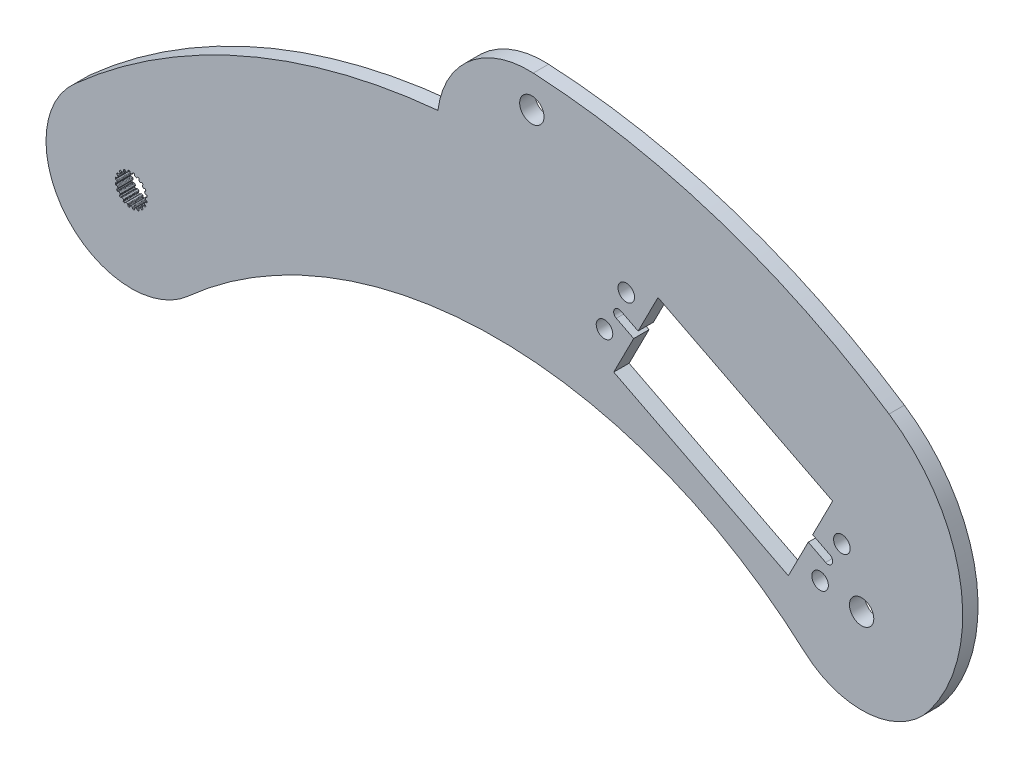
SolidWorks part; units mm, degrees
ref_plane "Front Plane" through (0, 0, 0) normal (0, 0, 1) x (1, 0, 0)
ref_plane "Top Plane" through (0, 0, 0) normal (0, 1, 0) x (1, 0, 0)
ref_plane "Right Plane" through (0, 0, 0) normal (1, 0, 0) x (0, 0, -1)
sketch "Sketch1" plane through (0, 0, 0) normal (0, 0, 1) x (1, 0, 0)
  line L0 (-0.1069, 2.9699) -> (0.1069, 2.9699)
  line L1 (0.3159, 3.2375) -> (0.2537, 3.0575)
  line L2 (-0.2964, 3.2367) -> (-0.2318, 3.0575)
  line L3 (-0.2964, 3.2367) -> (0.3159, 3.2375) construction
  line L4 (0, 3.3252) -> (0, 0) construction
  line L5 (-0.2318, 3.0575) -> (0.2537, 3.0575) construction
  line L6 (-0.4281, 3.3241) -> (0.4281, 3.3263) construction
  line L7 (0.7183, 3.1698) -> (0.7244, 2.9795)
  line L8 (0.816, 2.8576) -> (1.0195, 2.7915)
  line L9 (1.3009, 2.9815) -> (1.1862, 2.8295)
  line L10 (1.6627, 2.7927) -> (1.6097, 2.6099)
  line L11 (1.6591, 2.4655) -> (1.8322, 2.3398)
  line L12 (2.1585, 2.4335) -> (2.0025, 2.3245)
  line L13 (2.4443, 2.1423) -> (2.3374, 1.9847)
  line L14 (2.3398, 1.8322) -> (2.4655, 1.6591)
  line L15 (2.8049, 1.6474) -> (2.6228, 1.5919)
  line L16 (2.9866, 1.2821) -> (2.8363, 1.1653)
  line L17 (2.7915, 1.0195) -> (2.8576, 0.816)
  line L18 (3.1767, 0.7) -> (2.9863, 0.7035)
  line L19 (3.2367, 0.2964) -> (3.0575, 0.2318)
  line L20 (2.9699, 0.1069) -> (2.9699, -0.1069)
  line L21 (3.2375, -0.3159) -> (3.0575, -0.2537)
  line L22 (3.1698, -0.7183) -> (2.9795, -0.7244)
  line L23 (2.8576, -0.816) -> (2.7915, -1.0195)
  line L24 (2.9815, -1.3009) -> (2.8295, -1.1862)
  line L25 (2.7927, -1.6627) -> (2.6099, -1.6097)
  line L26 (2.4655, -1.6591) -> (2.3398, -1.8322)
  line L27 (2.4335, -2.1585) -> (2.3245, -2.0025)
  line L28 (2.1423, -2.4443) -> (1.9847, -2.3374)
  line L29 (1.8322, -2.3398) -> (1.6591, -2.4655)
  line L30 (1.6474, -2.8049) -> (1.5919, -2.6228)
  line L31 (1.2821, -2.9866) -> (1.1653, -2.8363)
  line L32 (1.0195, -2.7915) -> (0.816, -2.8576)
  line L33 (0.7, -3.1767) -> (0.7035, -2.9863)
  line L34 (0.2964, -3.2367) -> (0.2318, -3.0575)
  line L35 (0.1069, -2.9699) -> (-0.1069, -2.9699)
  line L36 (-0.3159, -3.2375) -> (-0.2537, -3.0575)
  line L37 (-0.7183, -3.1698) -> (-0.7244, -2.9795)
  line L38 (-0.816, -2.8576) -> (-1.0195, -2.7915)
  line L39 (-1.3009, -2.9815) -> (-1.1862, -2.8295)
  line L40 (-1.6627, -2.7927) -> (-1.6097, -2.6099)
  line L41 (-1.6591, -2.4655) -> (-1.8322, -2.3398)
  line L42 (-2.1585, -2.4335) -> (-2.0025, -2.3245)
  line L43 (-2.4443, -2.1423) -> (-2.3374, -1.9847)
  line L44 (-2.3398, -1.8322) -> (-2.4655, -1.6591)
  line L45 (-2.8049, -1.6474) -> (-2.6228, -1.5919)
  line L46 (-2.9866, -1.2821) -> (-2.8363, -1.1653)
  line L47 (-2.7915, -1.0195) -> (-2.8576, -0.816)
  line L48 (-3.1767, -0.7) -> (-2.9863, -0.7035)
  line L49 (-3.2367, -0.2964) -> (-3.0575, -0.2318)
  line L50 (-2.9699, -0.1069) -> (-2.9699, 0.1069)
  line L51 (-3.2375, 0.3159) -> (-3.0575, 0.2537)
  line L52 (-3.1698, 0.7183) -> (-2.9795, 0.7244)
  line L53 (-2.8576, 0.816) -> (-2.7915, 1.0195)
  line L54 (-2.9815, 1.3009) -> (-2.8295, 1.1862)
  line L55 (-2.7927, 1.6627) -> (-2.6099, 1.6097)
  line L56 (-2.4655, 1.6591) -> (-2.3398, 1.8322)
  line L57 (-2.4335, 2.1585) -> (-2.3245, 2.0025)
  line L58 (-2.1423, 2.4443) -> (-1.9847, 2.3374)
  line L59 (-1.8322, 2.3398) -> (-1.6591, 2.4655)
  line L60 (-1.6474, 2.8049) -> (-1.5919, 2.6228)
  line L61 (-1.2821, 2.9866) -> (-1.1653, 2.8363)
  line L62 (-1.0195, 2.7915) -> (-0.816, 2.8576)
  line L63 (-0.7, 3.1767) -> (-0.7035, 2.9863)
  line L64 (0.4281, 3.3263) -> (0.62, 3.2938)
  line L65 (1.4351, 3.0312) -> (1.6075, 2.9409)
  line L66 (2.3015, 2.4394) -> (2.4376, 2.3003)
  line L67 (2.9427, 1.6088) -> (3.0291, 1.4344)
  line L68 (3.2958, 0.6207) -> (3.3241, 0.4281)
  line L69 (3.3263, -0.4281) -> (3.2938, -0.62)
  line L70 (3.0312, -1.4351) -> (2.9409, -1.6075)
  line L71 (2.4394, -2.3015) -> (2.3003, -2.4376)
  line L72 (1.6088, -2.9427) -> (1.4344, -3.0291)
  line L73 (0.6207, -3.2958) -> (0.4281, -3.3241)
  line L74 (-0.4281, -3.3263) -> (-0.62, -3.2938)
  line L75 (-1.4351, -3.0312) -> (-1.6075, -2.9409)
  line L76 (-2.3015, -2.4394) -> (-2.4376, -2.3003)
  line L77 (-2.9427, -1.6088) -> (-3.0291, -1.4344)
  line L78 (-3.2958, -0.6207) -> (-3.3241, -0.4281)
  line L79 (-3.3263, 0.4281) -> (-3.2938, 0.62)
  line L80 (-3.0312, 1.4351) -> (-2.9409, 1.6075)
  line L81 (-2.4394, 2.3015) -> (-2.3003, 2.4376)
  line L82 (-1.6088, 2.9427) -> (-1.4344, 3.0291)
  line L83 (-0.6207, 3.2958) -> (-0.4281, 3.3241)
  line L84 (-11.8753, 13.2369) -> (11.8753, -13.2369) construction
  line L85 (164.2753, 13.2369) -> (140.5247, -13.2369) construction
  line L86 (0, 0) -> (152.4, 0) construction
  arc A0 (0.2537, 3.0575) -> (0.1069, 2.9699) centre (0.1283, 3.1009) cw
  arc A1 (-0.2318, 3.0575) -> (-0.1069, 2.9699) centre (-0.1069, 3.1026) ccw
  arc A2 (0.62, 3.2938) -> (0.7183, 3.1698) centre (0.5856, 3.1656) cw
  arc A3 (0.7244, 2.9795) -> (0.816, 2.8576) centre (0.857, 2.9838) ccw
  arc A4 (-0.4281, 3.3241) -> (-0.2964, 3.2367) centre (-0.4213, 3.1916) cw
  arc A5 (0.4281, 3.3263) -> (0.3159, 3.2375) centre (0.4413, 3.1942) ccw
  arc A6 (1.1862, 2.8295) -> (1.0195, 2.7915) centre (1.0802, 2.9095) cw
  arc A7 (1.4351, 3.0312) -> (1.3009, 2.9815) centre (1.4068, 2.9015) ccw
  arc A8 (1.6075, 2.9409) -> (1.6627, 2.7927) centre (1.5352, 2.8297) cw
  arc A9 (1.6097, 2.6099) -> (1.6591, 2.4655) centre (1.7371, 2.5729) ccw
  arc A10 (2.0025, 2.3245) -> (1.8322, 2.3398) centre (1.9264, 2.4332) cw
  arc A11 (2.3015, 2.4394) -> (2.1585, 2.4335) centre (2.2346, 2.3248) ccw
  arc A12 (2.4376, 2.3003) -> (2.4443, 2.1423) centre (2.3345, 2.2168) cw
  arc A13 (2.3374, 1.9847) -> (2.3398, 1.8322) centre (2.4472, 1.9102) ccw
  arc A14 (2.6228, 1.5919) -> (2.4655, 1.6591) centre (2.5841, 1.7189) cw
  arc A15 (2.9427, 1.6088) -> (2.8049, 1.6474) centre (2.8436, 1.5205) ccw
  arc A16 (3.0291, 1.4344) -> (2.9866, 1.2821) centre (2.9052, 1.3869) cw
  arc A17 (2.8363, 1.1653) -> (2.7915, 1.0195) centre (2.9177, 1.0605) ccw
  arc A18 (2.9863, 0.7035) -> (2.8576, 0.816) centre (2.9887, 0.8362) cw
  arc A19 (3.2958, 0.6207) -> (3.1767, 0.7) centre (3.1743, 0.5673) ccw
  arc A20 (3.3241, 0.4281) -> (3.2367, 0.2964) centre (3.1916, 0.4213) cw
  arc A21 (3.0575, 0.2318) -> (2.9699, 0.1069) centre (3.1026, 0.1069) ccw
  arc A22 (3.0575, -0.2537) -> (2.9699, -0.1069) centre (3.1009, -0.1283) cw
  arc A23 (3.3263, -0.4281) -> (3.2375, -0.3159) centre (3.1942, -0.4413) ccw
  arc A24 (3.2938, -0.62) -> (3.1698, -0.7183) centre (3.1656, -0.5856) cw
  arc A25 (2.9795, -0.7244) -> (2.8576, -0.816) centre (2.9838, -0.857) ccw
  arc A26 (2.8295, -1.1862) -> (2.7915, -1.0195) centre (2.9095, -1.0802) cw
  arc A27 (3.0312, -1.4351) -> (2.9815, -1.3009) centre (2.9015, -1.4068) ccw
  arc A28 (2.9409, -1.6075) -> (2.7927, -1.6627) centre (2.8297, -1.5352) cw
  arc A29 (2.6099, -1.6097) -> (2.4655, -1.6591) centre (2.5729, -1.7371) ccw
  arc A30 (2.3245, -2.0025) -> (2.3398, -1.8322) centre (2.4332, -1.9264) cw
  arc A31 (2.4394, -2.3015) -> (2.4335, -2.1585) centre (2.3248, -2.2346) ccw
  arc A32 (2.3003, -2.4376) -> (2.1423, -2.4443) centre (2.2168, -2.3345) cw
  arc A33 (1.9847, -2.3374) -> (1.8322, -2.3398) centre (1.9102, -2.4472) ccw
  arc A34 (1.5919, -2.6228) -> (1.6591, -2.4655) centre (1.7189, -2.5841) cw
  arc A35 (1.6088, -2.9427) -> (1.6474, -2.8049) centre (1.5205, -2.8436) ccw
  arc A36 (1.4344, -3.0291) -> (1.2821, -2.9866) centre (1.3869, -2.9052) cw
  arc A37 (1.1653, -2.8363) -> (1.0195, -2.7915) centre (1.0605, -2.9177) ccw
  arc A38 (0.7035, -2.9863) -> (0.816, -2.8576) centre (0.8362, -2.9887) cw
  arc A39 (0.6207, -3.2958) -> (0.7, -3.1767) centre (0.5673, -3.1743) ccw
  arc A40 (0.4281, -3.3241) -> (0.2964, -3.2367) centre (0.4213, -3.1916) cw
  arc A41 (0.2318, -3.0575) -> (0.1069, -2.9699) centre (0.1069, -3.1026) ccw
  arc A42 (-0.2537, -3.0575) -> (-0.1069, -2.9699) centre (-0.1283, -3.1009) cw
  arc A43 (-0.4281, -3.3263) -> (-0.3159, -3.2375) centre (-0.4413, -3.1942) ccw
  arc A44 (-0.62, -3.2938) -> (-0.7183, -3.1698) centre (-0.5856, -3.1656) cw
  arc A45 (-0.7244, -2.9795) -> (-0.816, -2.8576) centre (-0.857, -2.9838) ccw
  arc A46 (-1.1862, -2.8295) -> (-1.0195, -2.7915) centre (-1.0802, -2.9095) cw
  arc A47 (-1.4351, -3.0312) -> (-1.3009, -2.9815) centre (-1.4068, -2.9015) ccw
  arc A48 (-1.6075, -2.9409) -> (-1.6627, -2.7927) centre (-1.5352, -2.8297) cw
  arc A49 (-1.6097, -2.6099) -> (-1.6591, -2.4655) centre (-1.7371, -2.5729) ccw
  arc A50 (-2.0025, -2.3245) -> (-1.8322, -2.3398) centre (-1.9264, -2.4332) cw
  arc A51 (-2.3015, -2.4394) -> (-2.1585, -2.4335) centre (-2.2346, -2.3248) ccw
  arc A52 (-2.4376, -2.3003) -> (-2.4443, -2.1423) centre (-2.3345, -2.2168) cw
  arc A53 (-2.3374, -1.9847) -> (-2.3398, -1.8322) centre (-2.4472, -1.9102) ccw
  arc A54 (-2.6228, -1.5919) -> (-2.4655, -1.6591) centre (-2.5841, -1.7189) cw
  arc A55 (-2.9427, -1.6088) -> (-2.8049, -1.6474) centre (-2.8436, -1.5205) ccw
  arc A56 (-3.0291, -1.4344) -> (-2.9866, -1.2821) centre (-2.9052, -1.3869) cw
  arc A57 (-2.8363, -1.1653) -> (-2.7915, -1.0195) centre (-2.9177, -1.0605) ccw
  arc A58 (-2.9863, -0.7035) -> (-2.8576, -0.816) centre (-2.9887, -0.8362) cw
  arc A59 (-3.2958, -0.6207) -> (-3.1767, -0.7) centre (-3.1743, -0.5673) ccw
  arc A60 (-3.3241, -0.4281) -> (-3.2367, -0.2964) centre (-3.1916, -0.4213) cw
  arc A61 (-3.0575, -0.2318) -> (-2.9699, -0.1069) centre (-3.1026, -0.1069) ccw
  arc A62 (-3.0575, 0.2537) -> (-2.9699, 0.1069) centre (-3.1009, 0.1283) cw
  arc A63 (-3.3263, 0.4281) -> (-3.2375, 0.3159) centre (-3.1942, 0.4413) ccw
  arc A64 (-3.2938, 0.62) -> (-3.1698, 0.7183) centre (-3.1656, 0.5856) cw
  arc A65 (-2.9795, 0.7244) -> (-2.8576, 0.816) centre (-2.9838, 0.857) ccw
  arc A66 (-2.8295, 1.1862) -> (-2.7915, 1.0195) centre (-2.9095, 1.0802) cw
  arc A67 (-3.0312, 1.4351) -> (-2.9815, 1.3009) centre (-2.9015, 1.4068) ccw
  arc A68 (-2.9409, 1.6075) -> (-2.7927, 1.6627) centre (-2.8297, 1.5352) cw
  arc A69 (-2.6099, 1.6097) -> (-2.4655, 1.6591) centre (-2.5729, 1.7371) ccw
  arc A70 (-2.3245, 2.0025) -> (-2.3398, 1.8322) centre (-2.4332, 1.9264) cw
  arc A71 (-2.4394, 2.3015) -> (-2.4335, 2.1585) centre (-2.3248, 2.2346) ccw
  arc A72 (-2.3003, 2.4376) -> (-2.1423, 2.4443) centre (-2.2168, 2.3345) cw
  arc A73 (-1.9847, 2.3374) -> (-1.8322, 2.3398) centre (-1.9102, 2.4472) ccw
  arc A74 (-1.5919, 2.6228) -> (-1.6591, 2.4655) centre (-1.7189, 2.5841) cw
  arc A75 (-1.6088, 2.9427) -> (-1.6474, 2.8049) centre (-1.5205, 2.8436) ccw
  arc A76 (-1.4344, 3.0291) -> (-1.2821, 2.9866) centre (-1.3869, 2.9052) cw
  arc A77 (-1.1653, 2.8363) -> (-1.0195, 2.7915) centre (-1.0605, 2.9177) ccw
  arc A78 (-0.7035, 2.9863) -> (-0.816, 2.8576) centre (-0.8362, 2.9887) cw
  arc A79 (-0.6207, 3.2958) -> (-0.7, 3.1767) centre (-0.5673, 3.1743) ccw
  circle A80 centre (0, 0) radius 12.7 construction
  arc A81 (-11.8753, 13.2369) -> (164.2753, 13.2369) centre (76.2, -84.9368) cw
  arc A82 (11.8753, -13.2369) -> (140.5247, -13.2369) centre (76.2, -84.9368) cw
  arc A84 (-11.8753, 13.2369) -> (11.8753, -13.2369) centre (0, 0) ccw
  arc A85 (164.2753, 13.2369) -> (140.5247, -13.2369) centre (152.4, 0) cw
  point P14 (0, 2.9699)
  point P26 (0, 0)
  point P247 (0, 0)
  dimension "D4" = 0.1327
  dimension "D8" = 20
  dimension "D9" = 25.4
  dimension "D10" = 131.8914
  dimension "D1" = 2.9699
  dimension "D2" = 0.2139
  dimension "D3" = 0.1904
  dimension "D5" = 0.0877
  dimension "D6" = 0.4855
  dimension "D7" = 0.8563
  dimension "D11" = 35.5662
  dimension "D12" = 152.4
extrude "Boss-Extrude1" add sketch "Sketch1" along normal blind 3.2004
sketch "Sketch2" plane through (0, 0, 3.2004) normal (0, 0, 1) x (1, 0, 0)
  line L0 (132.2879, 12.7254) -> (132.9641, 14.0508) construction
  line L5 (128.1311, 26.252) -> (118.8966, 8.1515) construction
  line L7 (109.9175, 35.5442) -> (146.3447, 16.9598)
  line L13 (109.9175, 35.5442) -> (100.683, 17.4437)
  line L19 (98.7496, 24.2228) -> (103.2942, 33.1305) construction
  line L20 (143.7335, 1.273) -> (148.2781, 10.1807) construction
  line L24 (101.0219, 28.6767) -> (146.0058, 5.7268) construction
  line L30 (100.683, 17.4437) -> (137.1102, -1.1407)
  line L31 (146.3447, 16.9598) -> (137.1102, -1.1407)
  circle A7 centre (103.2942, 33.1305) radius 1.7272
  circle A9 centre (143.7335, 1.273) radius 1.7272
  circle A10 centre (148.2781, 10.1807) radius 1.7272
  circle A11 centre (98.7496, 24.2228) radius 1.7272
  circle A13 centre (132.2879, 12.7254) radius 3.429 construction
  arc A14 (0, 0) -> (152.4, 0) centre (76.2, -84.9368) cw construction
  arc A15 (-11.8753, 13.2369) -> (11.8753, -13.2369) centre (0, 0) ccw construction
  arc A16 (140.5247, -13.2369) -> (164.2753, 13.2369) centre (152.4, 0) ccw construction
  arc A17 (164.2753, 13.2369) -> (-11.8753, 13.2369) centre (76.2, -84.9368) ccw construction
  circle A18 centre (152.4, 0) radius 2.54
  point P0 (132.2879, 12.7254)
  point P1 (99.9946, 26.663)
  point P24 (123.5139, 17.2018)
  dimension "D2" = 15.4
  dimension "D3" = 6.858
  dimension "D5" = 3.4544
  dimension "D10" = 5.08
  dimension "D6" = 2.2606
  dimension "D8" = 20.32
  dimension "D13" = 23.7998
  dimension "D1" = 50.5
  dimension "D4" = 10
  dimension "D7" = 1.4879
  dimension "D9" = 40.894
extrude "Cut-Extrude1" cut sketch "Sketch2" against normal up to surface (3.2004 mm away) up to face at (76.2, 8.6481, 0)
sketch "Sketch3" plane through (0, 0, 3.2004) normal (0, 0, 1) x (1, 0, 0)
  line L0 (146.3447, 16.9598) -> (137.1102, -1.1407) construction
  line L1 (109.9175, 35.5442) -> (100.683, 17.4437) construction
  line L4 (102.1419, 29.2459) -> (105.762, 27.399)
  line L5 (102.1419, 29.2459) -> (101.2184, 27.4358) construction
  line L7 (101.2184, 27.4358) -> (104.8385, 25.5889)
  line L8 (105.762, 27.399) -> (104.8385, 25.5889)
  line L9 (142.1892, 8.8146) -> (145.8093, 6.9677)
  line L10 (142.1892, 8.8146) -> (141.2657, 7.0045)
  line L11 (141.2657, 7.0045) -> (144.8858, 5.1576)
  line L12 (145.8093, 6.9677) -> (144.8858, 5.1576) construction
  arc A6 (145.8093, 6.9677) -> (144.8858, 5.1576) centre (145.3475, 6.0627) cw
  arc A7 (102.1419, 29.2459) -> (101.2184, 27.4358) centre (101.6802, 28.3409) ccw
  point P22 (105.3003, 26.494)
  point P23 (141.7274, 7.9096)
  dimension "D4" = 4.064
  dimension "D5" = 2.032
extrude "Cut-Extrude2" cut sketch "Sketch3" against normal up to surface (3.2004 mm away) up to face at (97.0224, 24.2228, 0)
sketch "Sketch4" plane through (0, 0, 3.2004) normal (0, 0, 1) x (1, 0, 0)
  line L1 (83.5881, 56.2861) -> (152.4, 0) construction
  line L2 (83.5881, 56.2861) -> (83.1655, 46.7705) construction
  line L4 (158.1231, 38.5869) -> (166.6312, -10.6636) construction
  line L5 (83.89, 63.0847) -> (63.9945, 46.3886) construction
  arc A0 (63.9945, 46.3886) -> (83.89, 63.0847) centre (82.9016, 44.0604) cw
  arc A1 (164.2753, 13.2369) -> (-11.8753, 13.2369) centre (76.2, -84.9368) ccw construction
  circle A3 centre (152.4, 0) radius 2.54 construction
  circle A4 centre (83.5881, 56.2861) radius 2.54
  circle A5 centre (152.4, 0) radius 2.54 construction
  arc A6 (83.89, 63.0847) -> (158.1231, 38.5869) centre (76.2, -84.9368) cw
  arc A7 (166.6312, -10.6636) -> (164.2753, 13.2369) centre (152.4, 0) ccw
  arc A8 (164.2753, 13.2369) -> (63.9945, 46.3886) centre (76.2, -84.9368) ccw
  arc A9 (164.2753, 13.2369) -> (-11.8753, 13.2369) centre (76.2, -84.9368) ccw construction
  arc A10 (158.1231, 38.5869) -> (166.6312, -10.6636) centre (139.1275, 9.9453) cw
  arc A11 (140.5247, -13.2369) -> (164.2753, 13.2369) centre (152.4, 0) ccw construction
  point P3 (82.7663, 37.7814)
  dimension "D4" = 49.98
  dimension "D3" = 19.05
  dimension "D1" = 9.525
  dimension "D2" = 88.9
  dimension "D5" = 25.9729
extrude "Boss-Extrude2" add sketch "Sketch4" against normal up to surface (3.2004 mm away) up to face at (123.5139, 17.2018, 0)
sketch "Sketch5" plane through (0, 0, 0) normal (0, 0, -1) x (-1, 0, 0)
  line L0 (-107.4588, 59.9507) -> (-96.515, 45.5135)
  line L1 (-96.515, 45.5135) -> (-52.583, 44.8229)
  arc A0 (-107.4588, 59.9507) -> (-52.583, 44.8229) centre (-82.8478, 42.1322) cw
  arc A1 (-52.583, 44.8229) -> (-113.2282, 41.6501) centre (-82.8478, 42.1322) ccw construction
  arc A2 (-83.89, 63.0847) -> (-158.1231, 38.5869) centre (-76.2, -84.9368) ccw construction
  arc A3 (11.8753, 13.2369) -> (-63.9945, 46.3886) centre (-76.2, -84.9368) ccw construction
